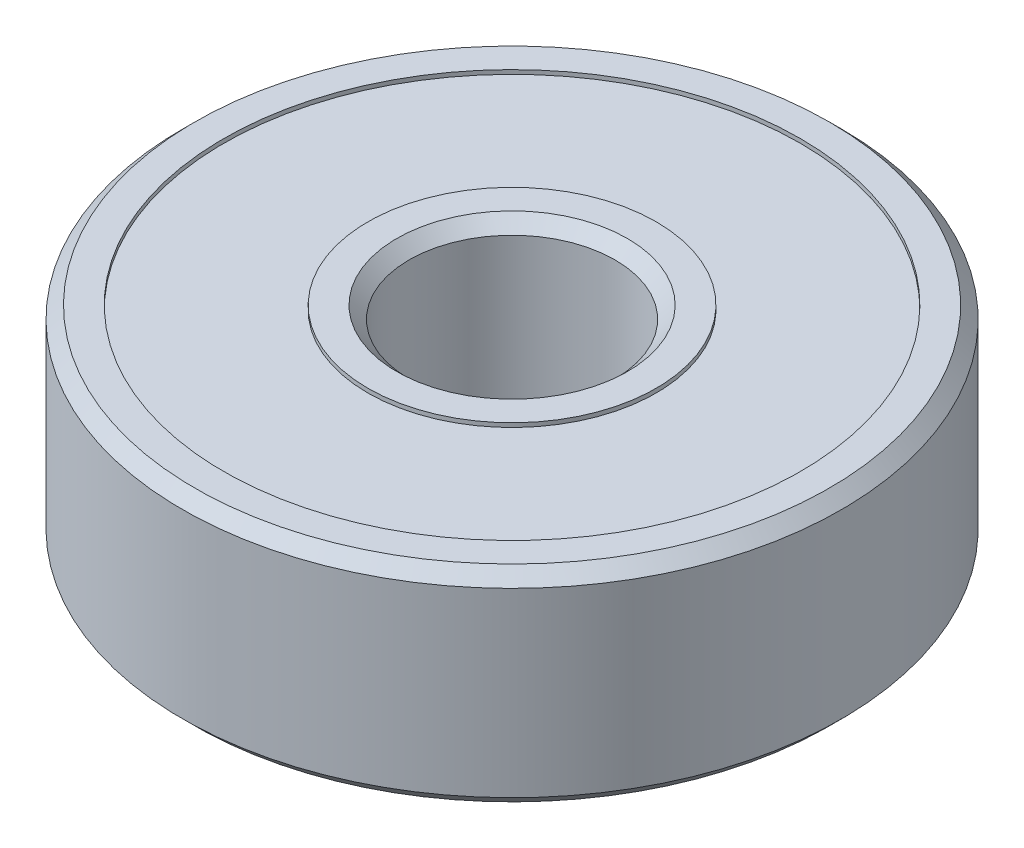
SolidWorks part; units mm, degrees
ref_plane "Plan de face" through (0, 0, 0) normal (0, 0, 1) x (1, 0, 0)
ref_plane "Plan de dessus" through (0, 0, 0) normal (0, 1, 0) x (1, 0, 0)
ref_plane "Plan de droite" through (0, 0, 0) normal (1, 0, 0) x (0, 0, -1)
sketch "Esquisse1" plane through (0, 0, 0) normal (0, 0, 1) x (1, 0, 0)
  line L0 (0, 0) -> (0, 31.1803) construction
  line L1 (2.5, -2.2) -> (2.5, 2.2)
  line L2 (2.8, 2.5) -> (3.5, 2.5)
  line L3 (3.5, 2.5) -> (3.5, 2.4)
  line L4 (3.5, 2.4) -> (7, 2.4)
  line L5 (7, 2.4) -> (7, 2.5)
  line L6 (7, 2.5) -> (7.7, 2.5)
  line L7 (8, 2.2) -> (8, -2.2)
  line L8 (0, 0) -> (8, 0) construction
  line L9 (2.5, 2.2) -> (2.8, 2.5)
  line L10 (7.7, 2.5) -> (8, 2.2)
  line L11 (7.7, -2.5) -> (8, -2.2)
  line L12 (7, -2.5) -> (7.7, -2.5)
  line L13 (7, -2.4) -> (7, -2.5)
  line L14 (3.5, -2.4) -> (7, -2.4)
  line L15 (3.5, -2.5) -> (3.5, -2.4)
  line L16 (2.8, -2.5) -> (3.5, -2.5)
  line L17 (2.5, -2.2) -> (2.8, -2.5)
  point P4 (2.5, 2.5)
  point P10 (8, 2.5)
  point P23 (2.5, 0)
  dimension "D1" = 0.1
  dimension "D2" = 5
  dimension "D3" = 5
  dimension "D4" = 1
  dimension "D5" = 1
  dimension "D6" = 16
revolve "Révolution2" add sketch "Esquisse1" angle 360 about L0
